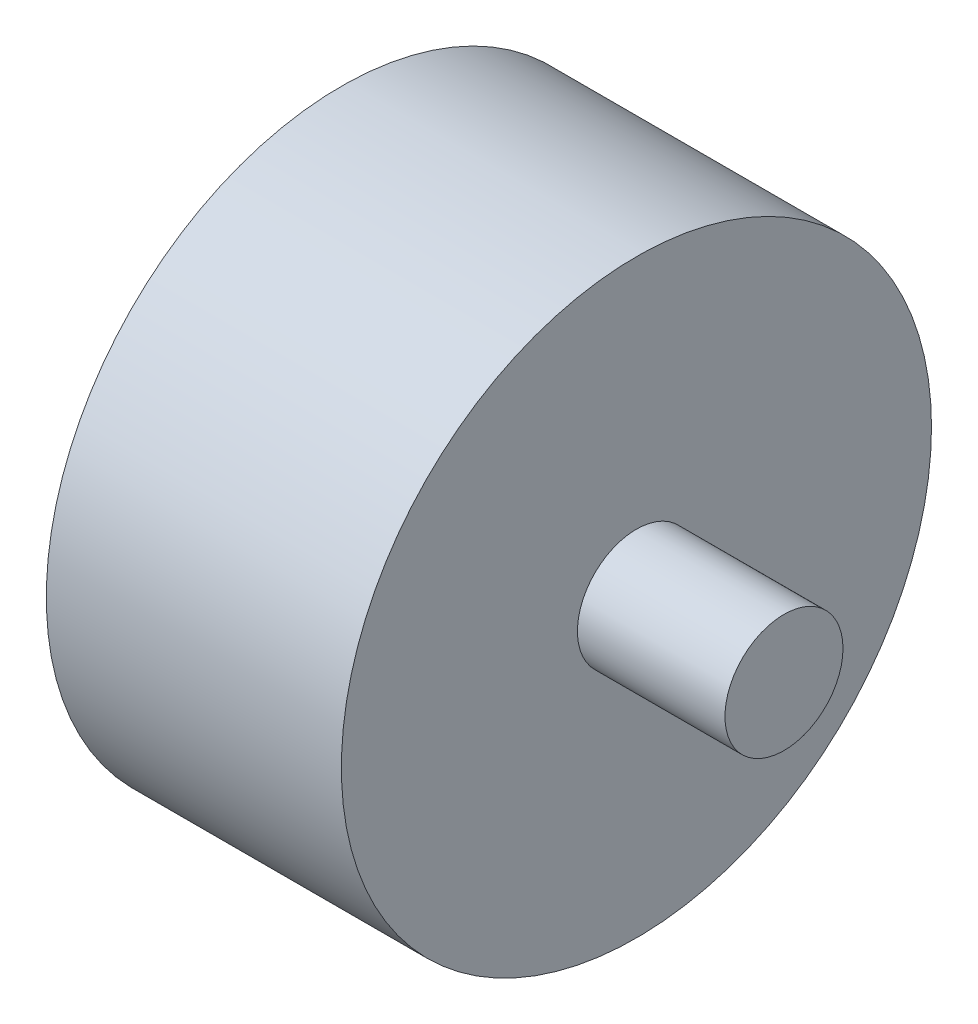
SolidWorks part; units mm, degrees
ref_plane "前视基准面" through (0, 0, 0) normal (0, 0, 1) x (1, 0, 0)
ref_plane "上视基准面" through (0, 0, 0) normal (0, 1, 0) x (1, 0, 0)
ref_plane "右视基准面" through (0, 0, 0) normal (1, 0, 0) x (0, 0, -1)
other "Configuration Table"
sketch "草图1" plane through (0, 0, 0) normal (0, 0, 1) x (1, 0, 0)
  line L0 (-10, 4) -> (-10, 0)
  line L1 (-10, 0) -> (30, 0)
  line L2 (30, 0) -> (30, 4)
  line L3 (30, 4) -> (20, 4)
  line L4 (20, 4) -> (20, 20)
  line L5 (20, 20) -> (0, 20)
  line L6 (0, 20) -> (0, 4)
  line L7 (0, 4) -> (-10, 4)
  line L8 (-10, 0) -> (30, 0) construction
  dimension "D1" = 10
  dimension "D2" = 30
  dimension "D3" = 40
  dimension "D4" = 4
  dimension "D5" = 20
revolve "旋转1" add sketch "草图1" angle 360 about L8
